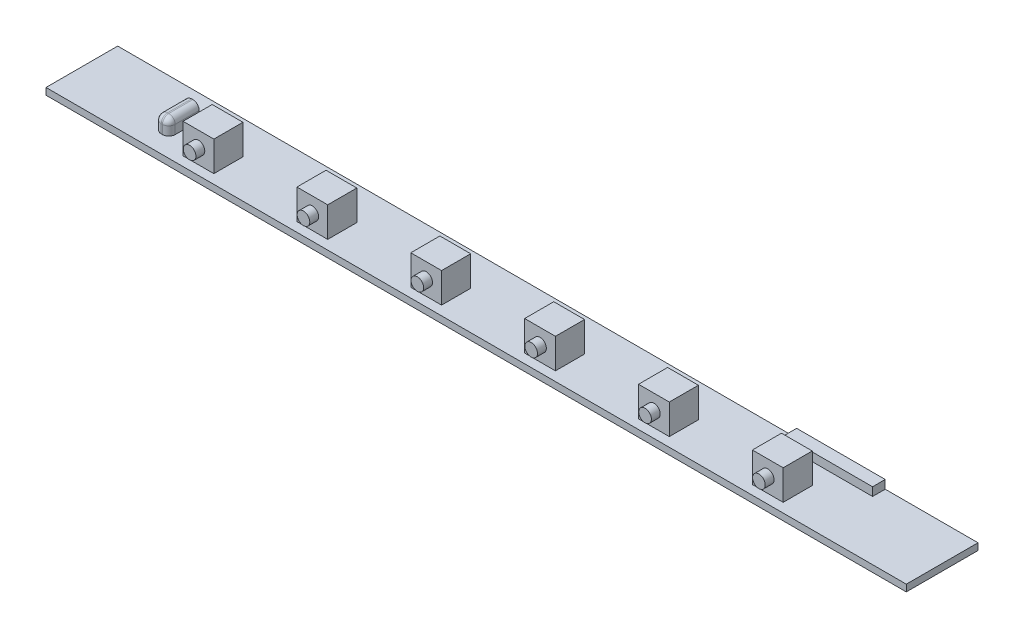
SolidWorks part; units mm, degrees
ref_plane "Front Plane" through (0, 0, 0) normal (0, 0, 1) x (1, 0, 0)
ref_plane "Top Plane" through (0, 0, 0) normal (0, 1, 0) x (1, 0, 0)
ref_plane "Right Plane" through (0, 0, 0) normal (1, 0, 0) x (0, 0, -1)
sketch "Sketch1" plane through (0, 0, 0) normal (0, 1, 0) x (1, 0, 0)
  line L1 (0, 0) -> (204, 0)
  line L2 (0, 0) -> (0, 17)
  line L3 (0, 17) -> (204, 17)
  line L4 (204, 0) -> (204, 17)
  dimension "D1" = 17
  dimension "D2" = 204
extrude "Boss-Extrude1" add sketch "Sketch1" along normal blind 1.6
sketch "Sketch2" plane through (0, 1.6, 0) normal (0, 1, 0) x (1, 0, 0)
  line L0 (204, 17) -> (0, 17) construction
  line L1 (30.3, 2.2) -> (37.6, 2.2)
  line L2 (30.3, 2.2) -> (30.3, 9.1)
  line L3 (30.3, 9.1) -> (37.6, 9.1)
  line L4 (37.6, 2.2) -> (37.6, 9.1)
  line L5 (0, 17) -> (0, 0) construction
  dimension "D1" = 7.3
  dimension "D2" = 6.9
  dimension "D3" = 7.9
  dimension "D4" = 30.3
extrude "Boss-Extrude2" add sketch "Sketch2" along normal blind 7.1
sketch "Sketch6" plane through (0, 0, -2.2) normal (0, 0, 1) x (1, 0, 0)
  circle A0 centre (33.95, 5.15) radius 1.5
  dimension "D1" = 3
extrude "Boss-Extrude6" add sketch "Sketch6" along normal blind 2.1
sketch "Sketch4" plane through (0, 1.6, 0) normal (0, 1, 0) x (1, 0, 0)
  line L3 (21.7006, 4.1184) -> (25.0006, 4.1184)
  line L4 (21.7006, 4.1184) -> (21.7006, 11.3184)
  line L5 (21.7006, 11.3184) -> (25.0006, 11.3184)
  line L6 (25.0006, 4.1184) -> (25.0006, 11.3184)
  dimension "D1" = 3.3
  dimension "D2" = 7.2
extrude "Boss-Extrude4" add sketch "Sketch4" along normal blind 3.6
sketch "Sketch5" plane through (0, 1.6, 0) normal (0, 1, 0) x (1, 0, 0)
  line L0 (204, 17) -> (0, 17) construction
  line L1 (182, 17) -> (161, 17)
  line L2 (182, 17) -> (182, 14)
  line L3 (182, 14) -> (161, 14)
  line L4 (161, 17) -> (161, 14)
  line L5 (204, 0) -> (204, 17) construction
  dimension "D1" = 21
  dimension "D2" = 3
  dimension "D3" = 22
extrude "Boss-Extrude5" add sketch "Sketch5" along normal blind 2
pattern_linear "LPattern1" count 6 spacing 27 along (1, 0, 0) of "Boss-Extrude6", "Boss-Extrude2"
fillet "Fillet1" radius 1.5 5 edges at (25.0006, 5.2, -7.7184) (21.7006, 5.2, -7.7184) (21.7006, 3.4, -4.1184) (25.0006, 3.4, -4.1184) (23.3506, 5.2, -4.1184)
